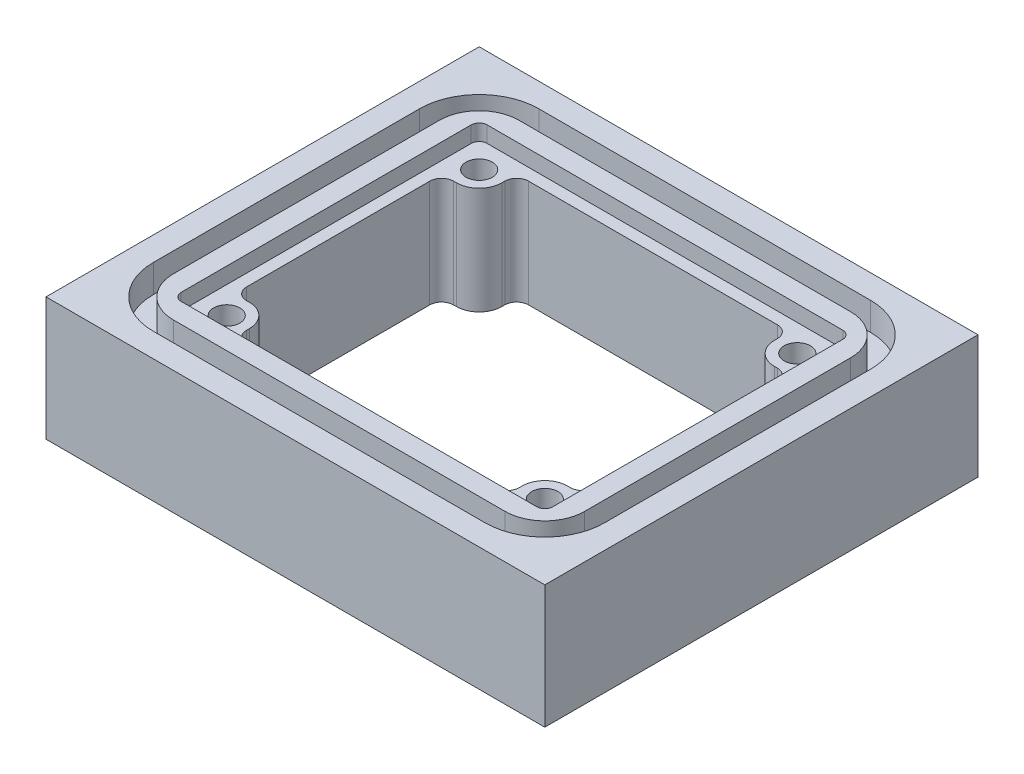
SolidWorks part; units mm, degrees
ref_plane "Front Plane" through (0, 0, 0) normal (0, 0, 1) x (1, 0, 0)
ref_plane "Top Plane" through (0, 0, 0) normal (0, 1, 0) x (1, 0, 0)
ref_plane "Right Plane" through (0, 0, 0) normal (1, 0, 0) x (0, 0, -1)
sketch "Sketch1" plane through (0, 0, 0) normal (0, 1, 0) x (1, 0, 0)
  line L0 (0, 18.7275) -> (0, -18.7275) construction
  line L1 (-22.8525, 18.7275) -> (22.8525, 18.7275) construction
  line L2 (-22.8525, 18.7275) -> (-22.8525, -18.7275) construction
  line L3 (-22.8525, -18.7275) -> (22.8525, -18.7275) construction
  line L4 (22.8525, 18.7275) -> (22.8525, -18.7275) construction
  line L5 (-22.8525, 18.7275) -> (22.8525, -18.7275) construction
  line L6 (-22.8525, -18.7275) -> (22.8525, 18.7275) construction
  line L7 (-22.8525, 0) -> (22.8525, 0) construction
  line L8 (-25.3525, 21.2275) -> (-25.3525, -21.2275) construction
  line L9 (-25.3525, -21.2275) -> (25.3525, -21.2275) construction
  line L10 (25.3525, 21.2275) -> (25.3525, -21.2275) construction
  line L11 (-25.3525, 21.2275) -> (25.3525, 21.2275) construction
  line L13 (21.8525, 13.0125) -> (21.8525, -13.0125)
  line L15 (-21.8525, 13.0125) -> (-21.8525, -13.0125)
  line L16 (-17.1375, 15.87) -> (-17.1375, 17.7275)
  line L17 (-19.995, 13.0125) -> (-21.8525, 13.0125)
  line L18 (-17.1375, 17.7275) -> (17.1375, 17.7275)
  line L19 (-21.8525, 17.7275) -> (21.8525, 17.7275) construction
  line L20 (-21.8525, 17.7275) -> (-21.8525, -17.7275) construction
  line L21 (19.995, 13.0125) -> (21.8525, 13.0125)
  line L22 (17.1375, 15.87) -> (17.1375, 17.7275)
  line L23 (-17.1375, -15.87) -> (-17.1375, -17.7275)
  line L24 (-19.995, -13.0125) -> (-21.8525, -13.0125)
  line L25 (19.995, -13.0125) -> (21.8525, -13.0125)
  line L26 (17.1375, -15.87) -> (17.1375, -17.7275)
  line L27 (-17.1375, -17.7275) -> (17.1375, -17.7275)
  line L28 (21.8525, 17.7275) -> (21.8525, -17.7275) construction
  line L29 (-21.8525, -17.7275) -> (21.8525, -17.7275) construction
  line L30 (31.3525, 27.2275) -> (31.3525, -27.2275)
  line L31 (-31.3525, -27.2275) -> (31.3525, -27.2275)
  line L32 (-31.3525, 27.2275) -> (-31.3525, -27.2275)
  line L33 (-31.3525, 27.2275) -> (31.3525, 27.2275)
  circle A0 centre (-19.995, 15.87) radius 1.6529
  circle A1 centre (19.995, 15.87) radius 1.6529
  circle A2 centre (19.995, -15.87) radius 1.6529
  circle A3 centre (-19.995, -15.87) radius 1.6529
  arc A5 (-19.995, 13.0125) -> (-17.1375, 15.87) centre (-19.995, 15.87) ccw
  arc A6 (19.995, 13.0125) -> (17.1375, 15.87) centre (19.995, 15.87) cw
  arc A7 (-19.995, -13.0125) -> (-17.1375, -15.87) centre (-19.995, -15.87) cw
  arc A8 (19.995, -13.0125) -> (17.1375, -15.87) centre (19.995, -15.87) ccw
  point P0 (0, 0)
  dimension "D5" = 3.3058
  dimension "D1" = 45.705
  dimension "D2" = 37.455
  dimension "D3" = 2.8575
  dimension "D4" = 2.8575
  dimension "D6" = 2.5
  dimension "D7" = 1
  dimension "D8" = 6
extrude "Boss-Extrude1" add sketch "Sketch1" along normal blind 15.5
sketch "Sketch2" plane through (0, 15.5, 0) normal (0, 1, 0) x (1, 0, 0)
  line L0 (-22.8525, 18.7275) -> (22.8525, 18.7275) construction
  line L1 (-22.8525, 18.7275) -> (-22.8525, -18.7275) construction
  line L2 (22.8525, 18.7275) -> (22.8525, -18.7275) construction
  line L3 (-22.8525, -18.7275) -> (22.8525, -18.7275) construction
  line L8 (-22.8525, 18.7275) -> (22.8525, 18.7275) construction
  line L9 (-22.8525, 18.7275) -> (-22.8525, -18.7275) construction
  line L10 (22.8525, 18.7275) -> (22.8525, -18.7275) construction
  line L11 (-22.8525, -18.7275) -> (22.8525, -18.7275) construction
  line L24 (-23.3525, -19.2275) -> (23.3525, -19.2275)
  line L25 (23.3525, 19.2275) -> (23.3525, -19.2275)
  line L26 (-23.3525, 19.2275) -> (23.3525, 19.2275)
  line L27 (-23.3525, 19.2275) -> (-23.3525, -19.2275)
  dimension "D1" = 0.5
extrude "Cut-Extrude1" cut sketch "Sketch2" against normal blind 2.024
fillet "Fillet2" radius 1.5 8 edges at (17.1375, 6.738, 17.7275) (21.8525, 6.738, 13.0125) (-17.1375, 6.738, 17.7275) (-21.8525, 6.738, 13.0125) (21.8525, 6.738, -13.0125) (17.1375, 6.738, -17.7275) (-21.8525, 6.738, -13.0125) (-17.1375, 6.738, -17.7275)
sketch "Sketch3" plane through (0, 15.5, 0) normal (0, 1, 0) x (1, 0, 0)
  line L10 (-28.3525, -24.2275) -> (28.3525, -24.2275)
  line L11 (28.3525, -24.2275) -> (28.3525, 24.2275)
  line L12 (28.3525, 24.2275) -> (-28.3525, 24.2275)
  line L13 (-28.3525, 24.2275) -> (-28.3525, -24.2275)
  line L14 (25.8525, -21.7275) -> (25.8525, 21.7275)
  line L15 (25.8525, 21.7275) -> (-25.8525, 21.7275)
  line L16 (-25.8525, 21.7275) -> (-25.8525, -21.7275)
  line L17 (-25.8525, -21.7275) -> (25.8525, -21.7275)
  line L18 (25.8525, -21.7275) -> (25.8525, 21.7275)
  line L19 (25.8525, 21.7275) -> (-25.8525, 21.7275)
  line L20 (-25.8525, 21.7275) -> (-25.8525, -21.7275)
  line L21 (-25.8525, -21.7275) -> (25.8525, -21.7275)
  dimension "D1" = 2.5
  dimension "D2" = 2.5
extrude "Cut-Extrude2" cut sketch "Sketch3" against normal blind 3.5 contours L10 L11 L12 L13 | L18 L19 L20 L21
fillet "Fillet3" radius 1 4 edges at (23.3525, 14.488, -19.2275) (-23.3525, 14.488, -19.2275) (-23.3525, 14.488, 19.2275) (23.3525, 14.488, 19.2275)
fillet "Fillet4" radius 5 4 edges at (25.8525, 13.75, -21.7275) (-25.8525, 13.75, -21.7275) (-25.8525, 13.75, 21.7275) (25.8525, 13.75, 21.7275)
fillet "Fillet5" radius 7.5 4 edges at (28.3525, 13.75, -24.2275) (-28.3525, 13.75, -24.2275) (-28.3525, 13.75, 24.2275) (28.3525, 13.75, 24.2275)
